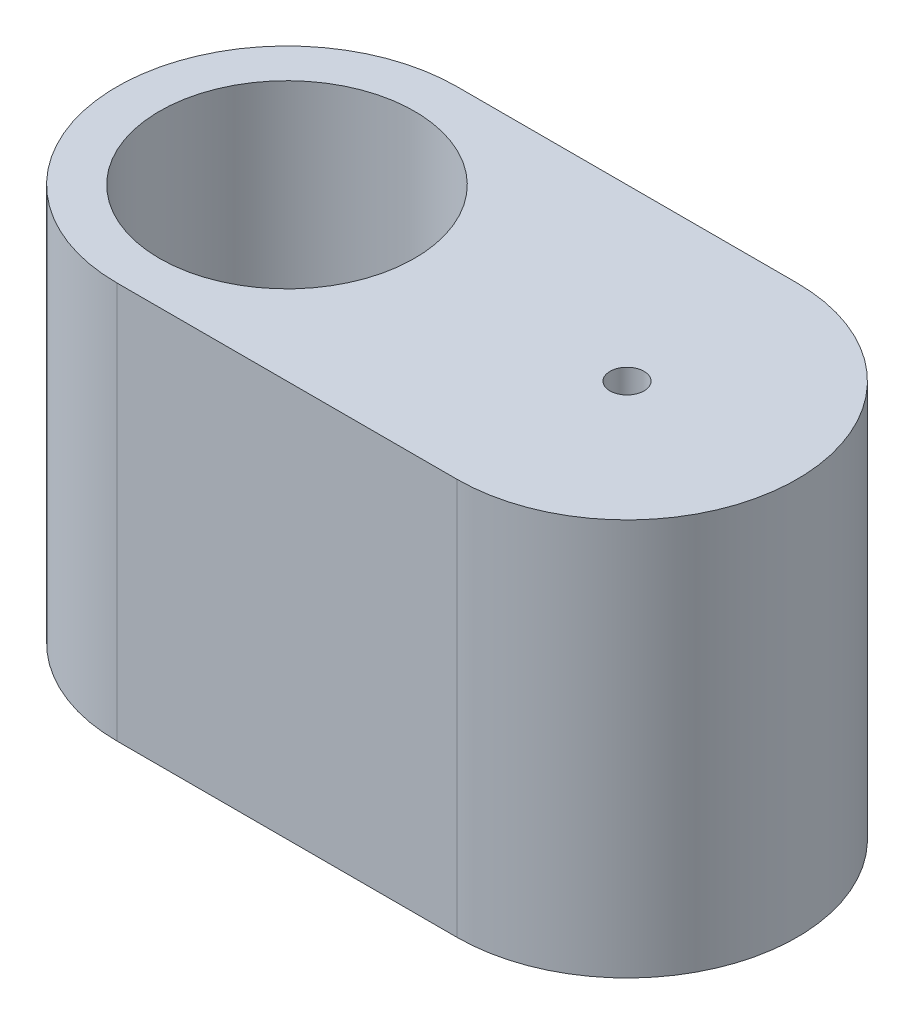
SolidWorks part; units mm, degrees
ref_plane "Front Plane" through (0, 0, 0) normal (0, 0, 1) x (1, 0, 0)
ref_plane "Top Plane" through (0, 0, 0) normal (0, 1, 0) x (1, 0, 0)
ref_plane "Right Plane" through (0, 0, 0) normal (1, 0, 0) x (0, 0, -1)
sketch "Sketch3" plane through (0, 0, 0) normal (0, 1, 0) x (1, 0, 0)
  line L0 (0, 0) -> (60, 0) construction
  line L1 (0, 30) -> (60, 30)
  line L2 (0, -30) -> (60, -30)
  line L4 (22.5, 0) -> (149.7196, 0) construction
  arc A0 (0, 30) -> (0, -30) centre (0, 0) ccw
  arc A1 (60, -30) -> (60, 30) centre (60, 0) ccw
  circle A2 centre (0, 0) radius 22.5
  point P3 (30, 0)
  dimension "D2" = 60
  dimension "D1" = 60
extrude "Boss-Extrude1" add sketch "Sketch3" along normal blind 70
sketch "Sketch4" plane through (0, 0, 0) normal (0, -1, 0) x (1, 0, 0)
  line L0 (0, 0) -> (100.3729, 0) construction
  line L1 (60, 30) -> (60, -30) construction
  circle A1 centre (60, 0) radius 6
extrude "Cut-Extrude1" cut sketch "Sketch4" against normal blind 2.5
sketch "Sketch6" plane through (0, 0, 0) normal (0, -1, 0) x (1, 0, 0)
  circle A1 centre (60, 0) radius 3
extrude "Cut-Extrude2" cut sketch "Sketch6" against normal blind 6
sketch "Sketch7" plane through (0, 70, 0) normal (0, 1, 0) x (1, 0, 0)
  circle A0 centre (60, 0) radius 3
extrude "Cut-Extrude3" cut sketch "Sketch7" against normal through all
